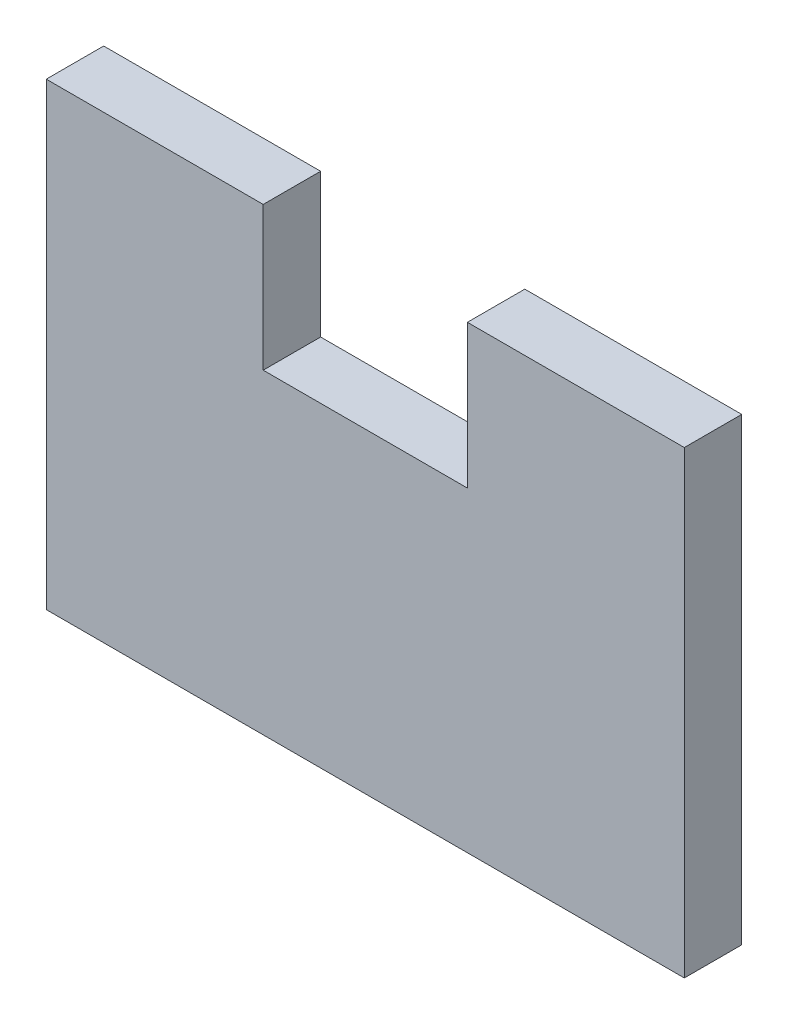
SolidWorks part; units mm, degrees
ref_plane "Front Plane" through (0, 0, 0) normal (0, 0, 1) x (1, 0, 0)
ref_plane "Top Plane" through (0, 0, 0) normal (0, 1, 0) x (1, 0, 0)
ref_plane "Right Plane" through (0, 0, 0) normal (1, 0, 0) x (0, 0, -1)
sketch "Sketch1" plane through (0, 0, 0) normal (0, 0, 1) x (1, 0, 0)
  line L1 (-100, 72) -> (100, 72)
  line L2 (-100, 72) -> (-100, -72)
  line L3 (-100, -72) -> (100, -72)
  line L4 (100, 72) -> (100, -72)
  line L5 (-100, 72) -> (100, -72) construction
  line L6 (-100, -72) -> (100, 72) construction
  point P0 (0, 0)
  dimension "D1" = 144
  dimension "D2" = 200
extrude "Boss-Extrude1" add sketch "Sketch1" along normal blind 18
sketch "Sketch2" plane through (0, 0, 18) normal (0, 0, 1) x (1, 0, 0)
  line L0 (100, 72) -> (-100, 72) construction
  line L1 (-32, 72) -> (32, 72)
  line L2 (-32, 72) -> (-32, 27)
  line L3 (-32, 27) -> (32, 27)
  line L4 (32, 72) -> (32, 27)
  line L5 (-100, -72) -> (100, -72) construction
  point P6 (0, -72)
  dimension "D1" = 64
  dimension "D2" = 45
  dimension "D3" = 32
extrude "Cut-Extrude1" cut sketch "Sketch2" against normal blind 18
